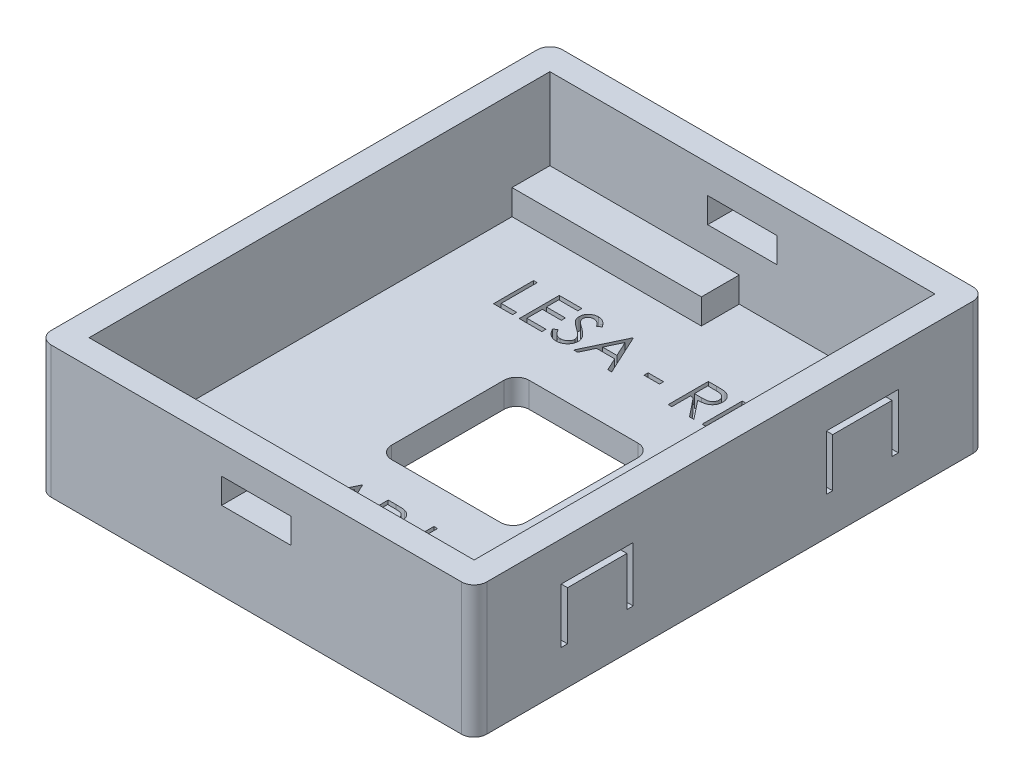
SolidWorks part; units mm, degrees
ref_plane "Front Plane" through (0, 0, 0) normal (0, 0, 1) x (1, 0, 0)
ref_plane "Top Plane" through (0, 0, 0) normal (0, 1, 0) x (1, 0, 0)
ref_plane "Right Plane" through (0, 0, 0) normal (1, 0, 0) x (0, 0, -1)
sketch "Sketch1" plane through (0, 0, 0) normal (0, 1, 0) x (1, 0, 0)
  line L1 (-17.25, 20.25) -> (17.25, 20.25)
  line L2 (-17.25, 20.25) -> (-17.25, -20.25)
  line L3 (-17.25, -20.25) -> (17.25, -20.25)
  line L4 (17.25, 20.25) -> (17.25, -20.25)
  line L5 (-17.25, 20.25) -> (17.25, -20.25) construction
  line L6 (-17.25, -20.25) -> (17.25, 20.25) construction
  point P0 (0, 0)
  dimension "D1" = 40.5
  dimension "D2" = 34.5
extrude "Boss-Extrude1" add sketch "Sketch1" along normal blind 10.45
sketch "Sketch4" plane through (0, 10.45, 0) normal (0, 1, 0) x (1, 0, 0)
  line L1 (-17.25, 20.25) -> (17.25, 20.25)
  line L2 (-17.25, 20.25) -> (-17.25, -20.25)
  line L3 (-17.25, -20.25) -> (17.25, -20.25)
  line L4 (17.25, 20.25) -> (17.25, -20.25)
  line L5 (-15.25, 18.25) -> (15.25, 18.25)
  line L6 (-15.25, 18.25) -> (-15.25, -18.25)
  line L7 (-15.25, -18.25) -> (15.25, -18.25)
  line L8 (15.25, 18.25) -> (15.25, -18.25)
  dimension "D1" = 2
  dimension "D2" = 2
  dimension "D3" = 2
  dimension "D4" = 2
extrude "Cut-Extrude2" cut sketch "Sketch4" against normal blind 8.45 contours L6 L5 L8 L7
sketch "Sketch7" plane through (0, 2, 0) normal (0, 1, 0) x (1, 0, 0)
  line L1 (15.25, -18.25) -> (12.25, -18.25)
  line L2 (15.25, -18.25) -> (15.25, -15.25)
  line L3 (15.25, -15.25) -> (12.25, -15.25)
  line L4 (12.25, -18.25) -> (12.25, -15.25)
  line L7 (15.25, 18.25) -> (13.25, 18.25)
  line L8 (15.25, 18.25) -> (15.25, 15.25)
  line L9 (15.25, 15.25) -> (13.25, 15.25)
  line L10 (13.25, 18.25) -> (13.25, 15.25)
  line L11 (-15.25, 18.25) -> (-0.25, 18.25)
  line L12 (-15.25, 18.25) -> (-15.25, 15.25)
  line L13 (-15.25, 15.25) -> (-0.25, 15.25)
  line L14 (-0.25, 18.25) -> (-0.25, 15.25)
  line L15 (-15.25, -18.25) -> (-5.25, -18.25)
  line L16 (-15.25, -18.25) -> (-15.25, -15.25)
  line L17 (-15.25, -15.25) -> (-5.25, -15.25)
  line L18 (-5.25, -18.25) -> (-5.25, -15.25)
  dimension "D1" = 3
  dimension "D2" = 3
  dimension "D3" = 3
  dimension "D4" = 2
  dimension "D5" = 3
  dimension "D6" = 15
  dimension "D7" = 3
  dimension "D8" = 10
extrude "Boss-Extrude2" add sketch "Sketch7" along normal blind 2
sketch "Sketch8" plane through (0, 2, 0) normal (0, 1, 0) x (1, 0, 0)
  line L0 (15.25, 15.25) -> (15.25, -15.25) construction
  line L1 (-3.35, -6.18) -> (5.27, -6.18)
  line L2 (-4.35, -5.18) -> (-4.35, 3.71)
  line L3 (-3.35, 4.71) -> (5.27, 4.71)
  line L4 (6.27, -5.18) -> (6.27, 3.71)
  line L5 (-0.25, 18.25) -> (13.25, 18.25) construction
  line L6 (-5.25, -18.25) -> (12.25, -18.25) construction
  line L7 (-15.25, 18.25) -> (-15.25, -18.25) construction
  arc A0 (5.27, -6.18) -> (6.27, -5.18) centre (5.27, -5.18) ccw
  arc A1 (-4.35, -5.18) -> (-3.35, -6.18) centre (-3.35, -5.18) ccw
  arc A2 (-3.35, 4.71) -> (-4.35, 3.71) centre (-3.35, 3.71) ccw
  arc A3 (6.27, 3.71) -> (5.27, 4.71) centre (5.27, 3.71) ccw
  dimension "D5" = 1
  dimension "D6" = 1
  dimension "D7" = 1
  dimension "D8" = 1
  dimension "D1" = 8.98
  dimension "D2" = 12.07
  dimension "D3" = 13.54
  dimension "D4" = 10.9
extrude "Cut-Extrude3" cut sketch "Sketch8" against normal blind 2
sketch "Sketch10" plane through (15.25, 0, 0) normal (-1, 0, 0) x (0, 0, 1)
  line L0 (-13.35, 3) -> (-13.35, 7.35)
  line L1 (-13.35, 7.35) -> (-7.65, 7.35)
  line L2 (-7.65, 7.35) -> (-7.65, 3)
  line L3 (-7.65, 3) -> (-8.15, 3)
  line L4 (-8.15, 3) -> (-8.15, 6.85)
  line L5 (-8.15, 6.85) -> (-12.85, 6.85)
  line L6 (-12.85, 6.85) -> (-12.85, 3)
  line L7 (-12.85, 3) -> (-13.35, 3)
  line L9 (7.65, 3) -> (7.65, 7.35)
  line L10 (7.65, 7.35) -> (13.35, 7.35)
  line L11 (13.35, 7.35) -> (13.35, 3)
  line L12 (-15.25, 2) -> (15.25, 2) construction
  line L13 (13.35, 3) -> (12.85, 3)
  line L14 (12.85, 3) -> (12.85, 6.85)
  line L15 (12.85, 6.85) -> (8.15, 6.85)
  line L16 (8.15, 6.85) -> (8.15, 3)
  line L17 (8.15, 3) -> (7.65, 3)
  line L19 (-18.25, 4) -> (-18.25, 10.45) construction
  line L21 (18.25, 4) -> (18.25, 10.45) construction
  dimension "D1" = 0.5
  dimension "D2" = 0.5
  dimension "D3" = 0.5
  dimension "D4" = 4.7
  dimension "D5" = 0.5
  dimension "D6" = 5.4
  dimension "D7" = 3.85
  dimension "D8" = 1
  dimension "D9" = 0.5
  dimension "D10" = 0.5
  dimension "D11" = 4.7
  dimension "D12" = 3.85
  dimension "D13" = 5.4
  dimension "D14" = 1
extrude "Cut-Extrude4" cut sketch "Sketch10" against normal blind 2
sketch "Sketch11" plane through (15.25, 0, 0) normal (-1, 0, 0) x (0, 0, 1)
  line L1 (-12.85, 6.85) -> (-8.15, 6.85)
  line L2 (-12.85, 6.85) -> (-12.85, 3)
  line L3 (-12.85, 3) -> (-8.15, 3)
  line L4 (-8.15, 6.85) -> (-8.15, 3)
  line L5 (8.15, 6.85) -> (12.85, 6.85)
  line L6 (8.15, 6.85) -> (8.15, 3)
  line L7 (8.15, 3) -> (12.85, 3)
  line L8 (12.85, 6.85) -> (12.85, 3)
extrude "Cut-Extrude5" cut sketch "Sketch11" against normal blind 0.6
fillet "Fillet1" radius 1 1 edges at (17.25, 5.225, 20.25)
fillet "Fillet2" radius 1 1 edges at (17.25, 5.225, -20.25)
fillet "Fillet3" radius 1 1 edges at (-17.25, 5.225, -20.25)
fillet "Fillet4" radius 1 1 edges at (-17.25, 5.225, 20.25)
sketch "Sketch13" plane through (0, 2, 0) normal (0, 1, 0) x (1, 0, 0)
  line L0 (-5.25, -18.25) -> (-5.25, -15.25) construction
  line L1 (-5.25, -18.25) -> (12.25, -18.25) construction
  text T0 "LESA - RPI"
  text T1 "APJ"
  dimension "D1" = 5.1714
  dimension "D2" = 26.7989
extrude "Cut-Extrude6" cut sketch "Sketch13" against normal blind 1
sketch "Sketch14" plane through (0, 0, -20.25) normal (0, 0, -1) x (-1, 0, 0)
  line L0 (-16.25, 10.45) -> (16.25, 10.45) construction
  line L1 (-2.75, 8.2) -> (2.75, 8.2)
  line L2 (-2.75, 8.2) -> (-2.75, 6.2)
  line L3 (-2.75, 6.2) -> (2.75, 6.2)
  line L4 (2.75, 8.2) -> (2.75, 6.2)
  point P6 (0, 10.45)
  point P7 (0, 8.2)
  dimension "D1" = 5.5
  dimension "D2" = 2.25
  dimension "D3" = 2
extrude "Cut-Extrude7" cut sketch "Sketch14" against normal blind 40.5
